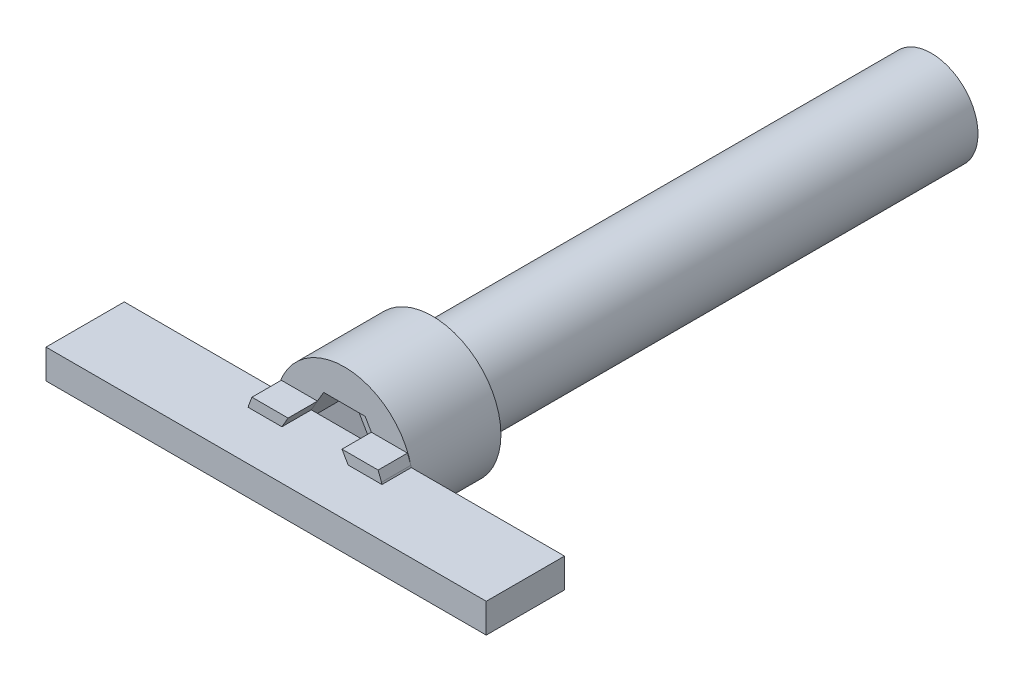
SolidWorks part; units mm, degrees
ref_plane "Plano frontal" through (0, 0, 0) normal (0, 0, 1) x (1, 0, 0)
ref_plane "Plano superior" through (0, 0, 0) normal (0, 1, 0) x (1, 0, 0)
ref_plane "Plano direito" through (0, 0, 0) normal (1, 0, 0) x (0, 0, -1)
sketch "Esboço1" plane through (0, 0, 0) normal (0, 0, 1) x (1, 0, 0)
  circle A0 centre (0, 0) radius 7
  dimension "D1" = 14
extrude "Ressalto-extrusão1" add sketch "Esboço1" along normal blind 9
sketch "Esboço2" plane through (0, 0, 0) normal (0, 0, -1) x (-1, 0, 0)
  circle A0 centre (0, 0) radius 4.765
  dimension "D1" = 9.53
extrude "Ressalto-extrusão2" add sketch "Esboço2" along normal blind 51
sketch "Esboço3" plane through (0, 0, 9) normal (0, 0, 1) x (1, 0, 0)
  line L1 (4.25, 0) -> (2.125, 3.6806)
  line L2 (2.125, 3.6806) -> (-2.125, 3.6806)
  line L3 (-2.125, 3.6806) -> (-4.25, 0)
  line L4 (-4.25, 0) -> (-2.125, -3.6806)
  line L5 (-2.125, -3.6806) -> (2.125, -3.6806)
  line L6 (2.125, -3.6806) -> (4.25, 0)
  circle A0 centre (0, 0) radius 3.6806 construction
  dimension "D1" = 8.5
extrude "Corte-extrusão1" cut sketch "Esboço3" against normal blind 5
sketch "Esboço4" plane through (0, 0, 9) normal (0, 0, 1) x (1, 0, 0)
  line L0 (22.5, 1.5) -> (-22.5, -1.5) construction
  line L1 (-22.5, 1.5) -> (22.5, 1.5)
  line L2 (-22.5, 1.5) -> (-22.5, -1.5)
  line L3 (-22.5, -1.5) -> (22.5, -1.5)
  line L4 (22.5, 1.5) -> (22.5, -1.5)
  dimension "D1" = 3
  dimension "D2" = 45
extrude "Ressalto-extrusão3" add sketch "Esboço4" along normal blind 8
sketch "Esboço5" plane through (0, 0, 9) normal (0, 0, 1) x (1, 0, 0)
  line L0 (-3.384, -1.5) -> (-2.125, -3.6806) construction
  line L1 (-6.8374, -1.5) -> (-3.384, -1.5)
  line L2 (2.7545, -2.5903) -> (3.384, -1.5)
  line L3 (-6.4503, -2.5903) -> (-2.7545, -2.5903)
  line L4 (6.8374, -1.5) -> (6.797, -1.6736)
  line L5 (2.125, -3.6806) -> (3.384, -1.5) construction
  line L6 (6.8374, -1.5) -> (3.384, -1.5)
  line L8 (6.4419, -2.5903) -> (2.7545, -2.5903)
  line L10 (-3.384, -1.5) -> (-2.7545, -2.5903)
  line L11 (-6.8374, -1.5) -> (-6.797, -1.6736)
  line L12 (-6.797, -1.6736) -> (-6.4503, -2.5903)
  line L13 (6.797, -1.6736) -> (6.4419, -2.5903)
  arc A1 (-6.8374, -1.5) -> (6.8374, -1.5) centre (0, 0) ccw construction
extrude "Ressalto-extrusão4" add sketch "Esboço5" along normal blind 3 separate body
sketch "Esboço7" plane through (0, 0, 9) normal (0, 0, 1) x (1, 0, 0)
  line L0 (3.384, 1.5) -> (2.125, 3.6806) construction
  line L1 (6.8374, 1.5) -> (3.384, 1.5)
  line L3 (6.4493, 2.5903) -> (2.7545, 2.5903)
  line L5 (-2.125, 3.6806) -> (-3.384, 1.5) construction
  line L6 (-6.8374, 1.5) -> (-3.384, 1.5)
  line L8 (-6.4472, 2.5903) -> (-2.7545, 2.5903)
  line L10 (6.8374, 1.5) -> (6.7951, 1.6813)
  line L11 (6.7951, 1.6813) -> (6.4493, 2.5903)
  line L12 (3.384, 1.5) -> (2.7545, 2.5903)
  line L13 (-2.7545, 2.5903) -> (-3.384, 1.5)
  line L14 (-6.8374, 1.5) -> (-6.7951, 1.6813)
  line L15 (-6.7951, 1.6813) -> (-6.4472, 2.5903)
  arc A0 (6.8374, 1.5) -> (-6.8374, 1.5) centre (0, 0) ccw construction
extrude "Ressalto-extrusão5" add sketch "Esboço7" along normal blind 3 separate body
